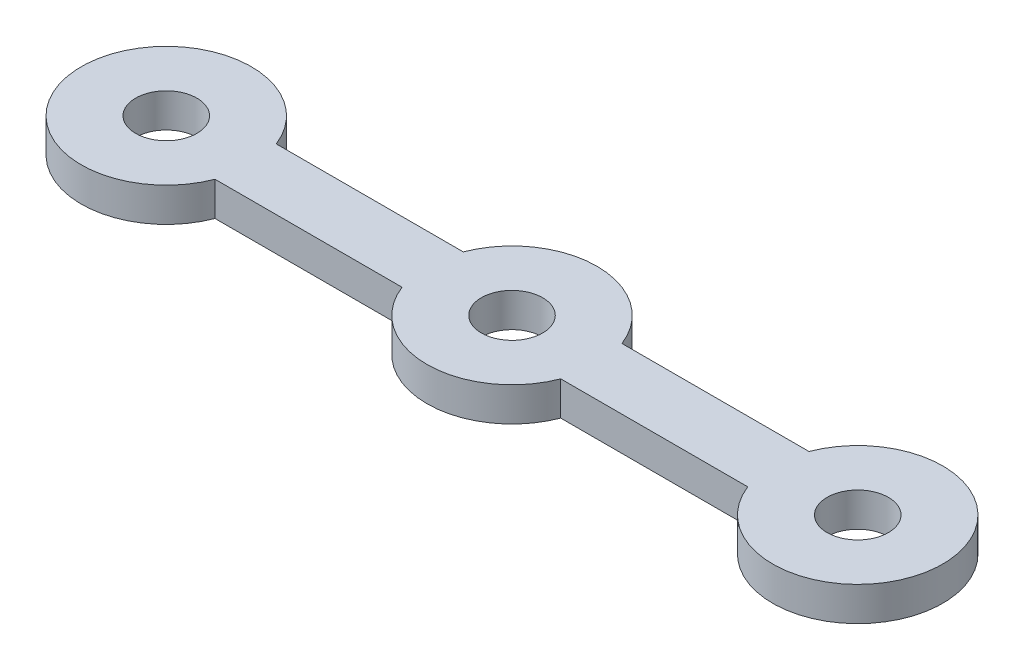
SolidWorks part; units mm, degrees
ref_plane "Front Plane" through (0, 0, 0) normal (0, 0, 1) x (1, 0, 0)
ref_plane "Top Plane" through (0, 0, 0) normal (0, 1, 0) x (1, 0, 0)
ref_plane "Right Plane" through (0, 0, 0) normal (1, 0, 0) x (0, 0, -1)
sketch "Sketch1" plane through (0, 0, 0) normal (0, 1, 0) x (1, 0, 0)
  line L0 (0, 0) -> (2032.46, 0) construction
  line L1 (233.2381, 90) -> (1799.2219, 90)
  line L2 (233.2381, -90) -> (1799.2219, -90)
  circle A0 centre (0, 0) radius 90
  circle A1 centre (1016.23, 0) radius 90
  circle A2 centre (2032.46, 0) radius 90
  circle A3 centre (0, 0) radius 250
  circle A4 centre (1016.23, 0) radius 250
  circle A5 centre (2032.46, 0) radius 250
  dimension "D2" = 500
  dimension "D3" = 180
  dimension "D4" = 180
  dimension "D1" = 2032.46
extrude "Boss-Extrude1" add sketch "Sketch1" along normal blind 100
